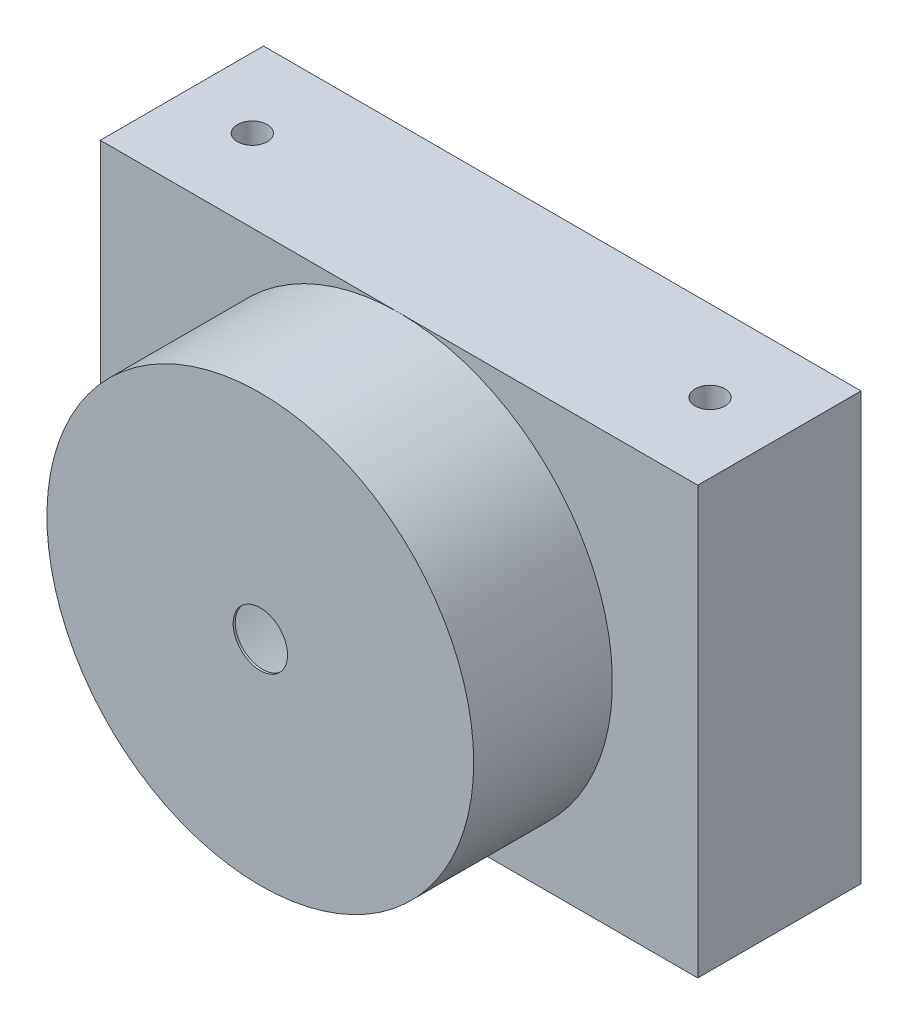
SolidWorks part; units mm, degrees
ref_plane "Plan de face" through (0, 0, 0) normal (0, 0, 1) x (1, 0, 0)
ref_plane "Plan de dessus" through (0, 0, 0) normal (0, 1, 0) x (1, 0, 0)
ref_plane "Plan de droite" through (0, 0, 0) normal (1, 0, 0) x (0, 0, -1)
sketch "Esquisse1" plane through (0, 0, 0) normal (0, 0, 1) x (1, 0, 0)
  line L1 (28, -20) -> (-28, -20)
  line L2 (28, -20) -> (28, 20)
  line L3 (28, 20) -> (-28, 20)
  line L4 (-28, -20) -> (-28, 20)
  line L5 (28, -20) -> (-28, 20) construction
  line L6 (28, 20) -> (-28, -20) construction
  point P0 (0, 0)
  dimension "D1" = 40
  dimension "D2" = 56
extrude "Boss.-Extru.1" add sketch "Esquisse1" along normal blind 15.3
sketch "Esquisse2" plane through (0, 0, 15.3) normal (0, 0, 1) x (1, 0, 0)
  circle A0 centre (0, 0) radius 20
extrude "Boss.-Extru.2" add sketch "Esquisse2" along normal blind 13
sketch "Esquisse3" plane through (0, 0, 28.3) normal (0, 0, 1) x (1, 0, 0)
  circle A0 centre (0, 0) radius 2.55
sketch "Esquisse5" plane through (0, 20, 0) normal (0, 1, 0) x (1, 0, 0)
  line L2 (28, 0) -> (-28, 0) construction
  line L3 (-28, -15.3) -> (-28, 0) construction
  line L4 (28, -15.3) -> (28, 0) construction
  circle A0 centre (-21.45, -7.6) radius 1.4
  circle A1 centre (21.45, -7.6) radius 1.4
  dimension "D1" = 7.6
  dimension "D3" = 6.55
  dimension "D2" = 6.55
extrude "Enlèv. mat.-Extru.1" cut sketch "Esquisse5" against normal blind 5
sketch "Esquisse6" plane through (0, 0, 0) normal (0, 0, -1) x (-1, 0, 0)
  circle A0 centre (0, 0) radius 16
extrude "Enlèv. mat.-Extru.2" cut sketch "Esquisse6" against normal blind 28.1
extrude "Enlèv. mat.-Extru.3" cut sketch "Esquisse3" against normal blind 28
